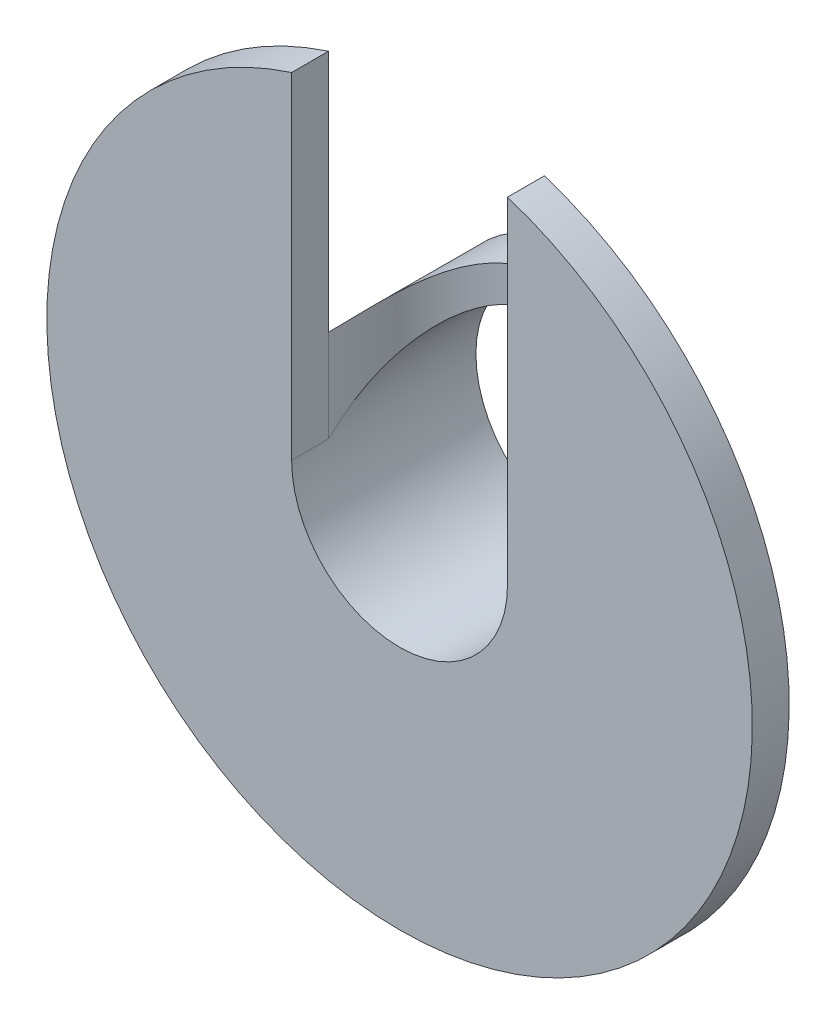
SolidWorks part; units mm, degrees
ref_plane "Plan de face" through (0, 0, 0) normal (0, 0, 1) x (1, 0, 0)
ref_plane "Plan de dessus" through (0, 0, 0) normal (0, 1, 0) x (1, 0, 0)
ref_plane "Plan de droite" through (0, 0, 0) normal (1, 0, 0) x (0, 0, -1)
sketch "Esquisse1" plane through (0, 0, 0) normal (0, 0, 1) x (1, 0, 0)
  line L0 (4.1, 0) -> (4.1, 12.7574)
  line L1 (-4.1, 0) -> (-4.1, 12.7574)
  arc A0 (-4.1, 12.7574) -> (4.1, 12.7574) centre (0, 0) ccw
  arc A1 (-4.1, 0) -> (4.1, 0) centre (0, 0) ccw
  dimension "D1" = 26.8
  dimension "D2" = 8.2
extrude "Boss.-Extru.1" add sketch "Esquisse1" along normal blind 1.4
sketch "Esquisse2" plane through (0, 0, 1.4) normal (0, 0, 1) x (1, 0, 0)
  circle A0 centre (0, 0) radius 5.4
  circle A2 centre (0, 0) radius 4.1
  dimension "D1" = 10.8
extrude "Boss.-Extru.2" add sketch "Esquisse2" against normal blind 7
sketch "Esquisse3" plane through (0, 0, 0) normal (0, 1, 0) x (1, 0, 0)
  line L0 (-4.1, -1.4) -> (-4.1, 0) construction
  line L1 (4.1, -1.4) -> (4.1, 0) construction
  line L2 (-4.1, -1.4) -> (4.1, -1.4) construction
  line L3 (-4.1, -1.4) -> (-4.1, 0)
  line L4 (4.1, -1.4) -> (4.1, 0)
  line L5 (-4.1, -1.4) -> (4.1, -1.4)
  arc A0 (-4.1, 0) -> (4.1, 0) centre (0, 0) cw
extrude "Enlèv. mat.-Extru.1" cut sketch "Esquisse3" along normal blind 7
